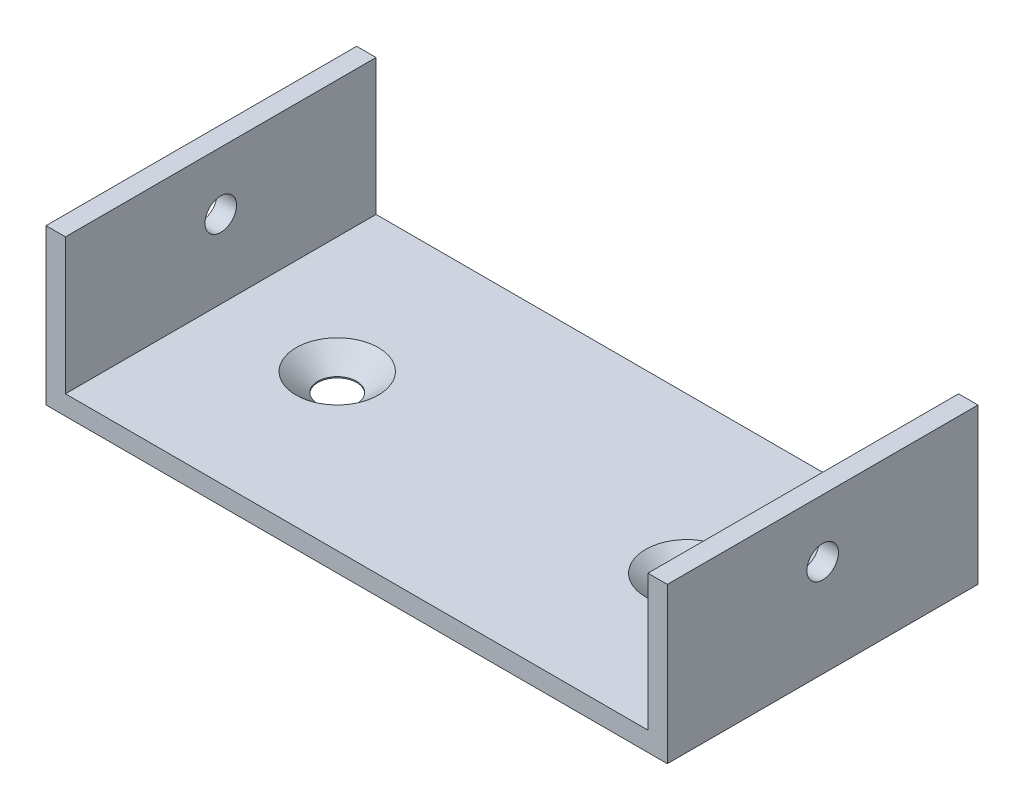
SolidWorks part; units mm, degrees
ref_plane "Front" through (0, 0, 0) normal (0, 0, 1) x (1, 0, 0)
ref_plane "Top" through (0, 0, 0) normal (0, 1, 0) x (1, 0, 0)
ref_plane "Right" through (0, 0, 0) normal (1, 0, 0) x (0, 0, -1)
sketch "Sketch1" plane through (0, 0, 0) normal (0, 0, 1) x (1, 0, 0)
  line L0 (0, -12.7) -> (0, 12.7) construction
  line L1 (-50.8, 0) -> (50.8, 0) construction
  line L2 (47.625, 12.7) -> (-47.625, 12.7) construction
  line L3 (-50.8, -12.7) -> (50.8, -12.7)
  line L4 (-50.8, -12.7) -> (-50.8, 12.7)
  line L5 (-50.8, 12.7) -> (50.8, 12.7)
  line L6 (50.8, -12.7) -> (50.8, 12.7)
  line L7 (-50.8, -12.7) -> (50.8, 12.7) construction
  line L8 (-50.8, 12.7) -> (50.8, -12.7) construction
  line L9 (-47.625, -12.7) -> (47.625, -12.7)
  point P3 (0, 0)
  point P4 (0, 0)
  point P8 (0, 0)
  point P13 (50.8, -9.525)
  point P17 (0, 12.7)
  point P20 (0, -12.7)
  dimension "Outside Width" = 101.6
  dimension "Outside Height" = 25.4
  dimension "Inside Height" = 22.225
  dimension "Wall Thickness" = 3.175
  dimension "Inside Width" = 95.25
sketch "Sketch2" plane through (0, 0, 0) normal (1, 0, 0) x (0, 0, -1)
  line L0 (-25.4, 0) -> (25.4, 0) construction
  dimension "Length" = 50.8
sketch "Sketch3" plane through (0, 0, 0) normal (0, 0, 1) x (1, 0, 0)
  line L0 (-50.8, 12.7) -> (-50.8, -12.7)
  line L1 (-50.8, -12.7) -> (50.8, -12.7)
  line L2 (50.8, -12.7) -> (50.8, 12.7)
  line L3 (50.8, 12.7) -> (47.625, 12.7)
  line L4 (47.625, 12.7) -> (47.625, -9.525)
  line L5 (47.625, -9.525) -> (-47.625, -9.525)
  line L6 (-47.625, -9.525) -> (-47.625, 12.7)
  line L7 (-47.625, 12.7) -> (-50.8, 12.7)
  line L8 (-47.625, -9.525) -> (-47.625, -12.7) construction
  dimension "D1" = 25.4
  dimension "D2" = 101.6
  dimension "D3" = 3.175
extrude "Boss-Extrude2" add sketch "Sketch3" along normal mid plane 50.8
sketch "Reference Sketch1" plane through (0, 0, 0) normal (1, 0, 0) x (0, 0, -1)
  line L0 (-25.4, 0) -> (25.4, 0) construction
  point P0 (19.05, 0)
  point P1 (-19.05, 0)
  dimension "D1" = 44.45
  dimension "D2" = 44.45
sketch "Sketch4" plane through (0, -9.525, 0) normal (0, 1, 0) x (1, 0, 0)
  line L0 (-47.625, 0) -> (-28.575, 0)
  line L1 (-47.625, -25.4) -> (-47.625, 25.4) construction
  line L2 (47.625, 0) -> (28.575, 0)
  line L3 (47.625, -25.4) -> (47.625, 25.4) construction
hole_wizard "1/4 (0.25) Diameter Hole1" positions "Sketch5" profile "Sketch6" hole size "1/4" standard "ANSI Inch" end condition through all
sketch "Sketch5" plane through (0, -9.525, 0) normal (0, 1, 0) x (1, 0, 0)
  point P0 (-28.575, 0)
  point P3 (28.575, 0)
sketch "Sketch6" plane through (-28.575, -9.525, 0) normal (1, 0, 0) x (0, 0, 1)
  line L0 (0, 0) -> (0, 3.175)
  line L1 (0, 3.175) -> (3.175, 3.175)
  line L2 (3.175, 3.175) -> (3.175, 2.9838)
  line L3 (3.175, 2.9838) -> (6.731, 0)
  line L5 (6.731, 0) -> (0, 0)
  line L6 (-3.175, 2.9838) -> (-6.731, 0) construction
  line L11 (0, -6.35) -> (0, 107.95) construction
  dimension "Thru Hole Dia." = 6.35
  dimension "Thru Hole Depth" = 3.175
  dimension "Near C'Sink Dia." = 13.462
  dimension "Near C'Sink Angle" = 100
sketch "Sketch7" plane through (50.8, 0, 0) normal (1, 0, 0) x (0, 0, -1)
  line L0 (0, -9.4842) -> (0, 3.2158)
hole_wizard "13/64 (0.20313) Diameter Hole1" positions "Sketch8" profile "Sketch9" hole size "13/64" standard "ANSI Inch" end condition through all
sketch "Sketch8" plane through (50.8, 0, 0) normal (1, 0, 0) x (0, 0, -1)
  point P0 (0, 3.2158)
sketch "Sketch9" plane through (50.8, 3.2158, 0) normal (0, 1, 0) x (0, 0, -1)
  line L0 (0, 0) -> (0, 101.6)
  line L1 (0, 101.6) -> (2.5798, 101.6)
  line L2 (2.5798, 101.6) -> (2.5798, 0)
  line L5 (2.5798, 0) -> (0, 0)
  line L11 (0, -6.35) -> (0, 107.95) construction
  dimension "Thru Hole Dia." = 5.1595
  dimension "Thru Hole Depth" = 101.6
equation "\"D1@Sketch3\" = \"Outside Height@Sketch1\""
equation "\"D2@Sketch3\" = \"Outside Width@Sketch1\""
equation "\"D3@Sketch3\" = \"Wall Thickness@Sketch1\""
equation "\"D1@Reference Sketch1\"=\"Outside Height@Sketch1\" * 1.75"
equation "\"D2@Reference Sketch1\" = \"D1@Reference Sketch1\""
equation "\"D1@Boss-Extrude2\" = \"Length@Sketch2\""
equation "\"Inside Height@Sketch1\"=\"Outside Height@Sketch1\"-\"Wall Thickness@Sketch1\""
equation "\"Inside Width@Sketch1\"=\"Outside Width@Sketch1\"-\"Wall Thickness@Sketch1\"*2"
